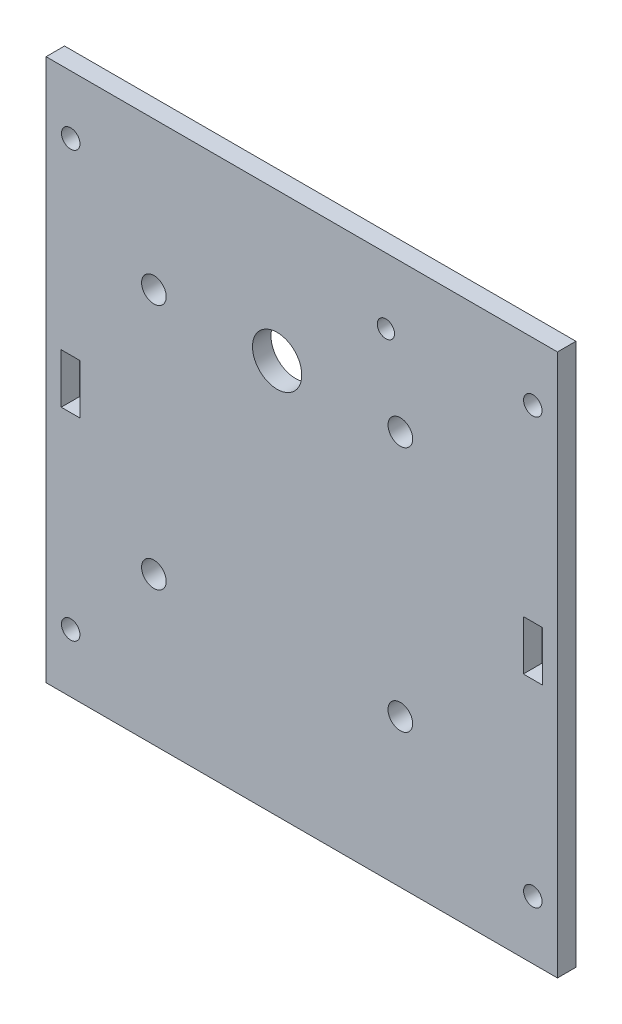
SolidWorks part; units mm, degrees
ref_plane "前视基准面" through (0, 0, 0) normal (0, 0, 1) x (1, 0, 0)
ref_plane "上视基准面" through (0, 0, 0) normal (0, 1, 0) x (1, 0, 0)
ref_plane "右视基准面" through (0, 0, 0) normal (1, 0, 0) x (0, 0, -1)
sketch "草图1" plane through (0, 0, 0) normal (0, 0, 1) x (1, 0, 0)
  line L1 (15.8468, 21.6171) -> (15.8468, -47.3829) construction
  line L3 (-59.1532, -47.3829) -> (-59.1532, 21.6171) construction
  line L8 (-25.6532, 21.6171) -> (-25.6532, -47.3829) construction
  line L9 (-25.6532, -12.8829) -> (-5.6532, -12.8829) construction
  line L10 (-5.6532, -12.8829) -> (-5.6532, -32.8829) construction
  line L11 (-45.6532, 7.1171) -> (-5.6532, 7.1171) construction
  line L12 (-63.1532, 31.1171) -> (-63.1532, -56.8829)
  line L13 (19.8468, -56.8829) -> (19.8468, 31.1171)
  line L15 (-60.6932, -8.8429) -> (-57.6132, -8.8429)
  line L16 (-60.6932, -8.8429) -> (-60.6932, -16.9229)
  line L17 (-60.6932, -16.9229) -> (-57.6132, -16.9229)
  line L18 (-63.1532, 31.1171) -> (19.8468, 31.1171)
  line L19 (19.8468, -56.8829) -> (-63.1532, -56.8829)
  line L20 (-57.6132, -8.8429) -> (-57.6132, -16.9229)
  line L21 (14.3068, -8.8429) -> (17.3868, -8.8429)
  line L22 (14.3068, -8.8429) -> (14.3068, -16.9229)
  line L23 (14.3068, -16.9229) -> (17.3868, -16.9229)
  line L24 (17.3868, -8.8429) -> (17.3868, -16.9229)
  line L25 (14.3068, -8.8429) -> (17.3868, -16.9229) construction
  line L26 (14.3068, -16.9229) -> (17.3868, -8.8429) construction
  circle A0 centre (-59.1532, 21.6171) radius 1.5
  circle A1 centre (15.8468, 21.6171) radius 1.5
  circle A2 centre (-59.1532, -47.3829) radius 1.5
  circle A3 centre (15.8468, -47.3829) radius 1.5
  circle A4 centre (-5.6532, -32.8829) radius 2
  circle A8 centre (-45.6532, -32.8829) radius 2
  circle A9 centre (-45.6532, 7.1171) radius 2
  circle A10 centre (-5.6532, 7.1171) radius 2
  circle A11 centre (-25.6532, 7.1171) radius 4
  circle A13 centre (-7.9984, 20.4417) radius 1.4004
  point P1 (-59.1532, -12.8829)
  point P33 (15.8468, -12.8829)
  dimension "D3" = 4
extrude "凸台-拉伸1" add sketch "草图1" along normal blind 3
